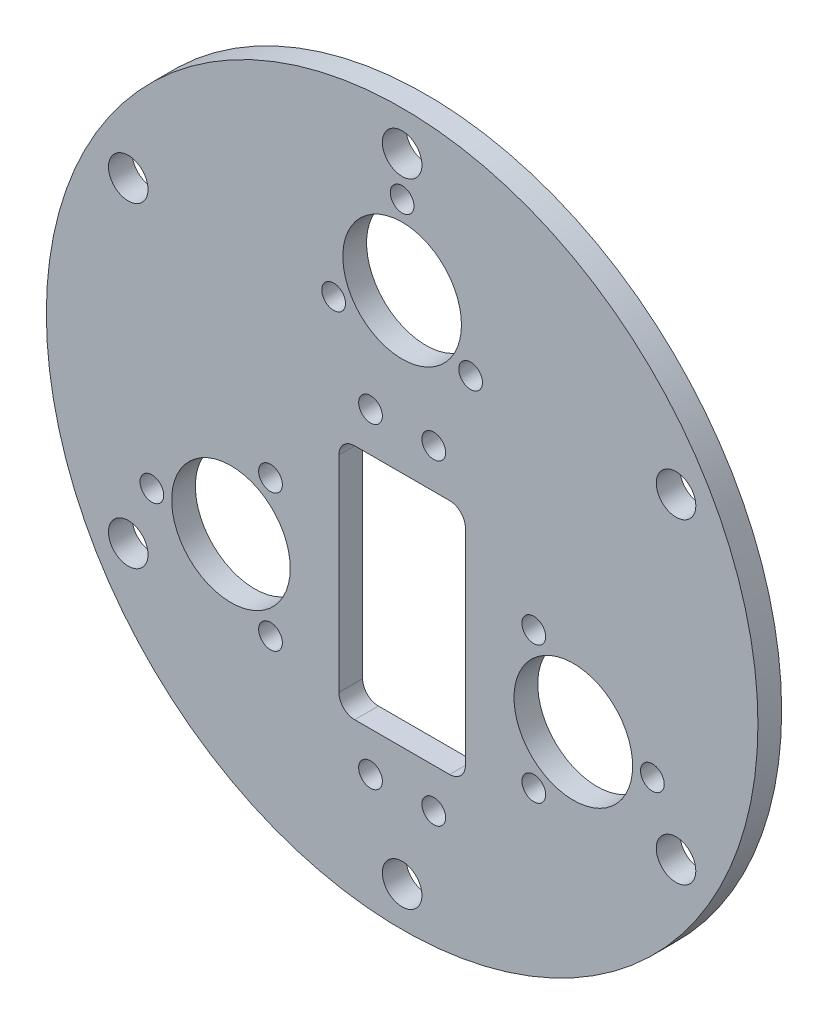
SolidWorks part; units mm, degrees
ref_plane "Front Plane" through (0, 0, 0) normal (0, 0, 1) x (1, 0, 0)
ref_plane "Top Plane" through (0, 0, 0) normal (0, 1, 0) x (1, 0, 0)
ref_plane "Right Plane" through (0, 0, 0) normal (1, 0, 0) x (0, 0, -1)
sketch "Sketch1" plane through (0, 0, 0) normal (0, 0, 1) x (1, 0, 0)
  circle A0 centre (0, 0) radius 4.5
  circle A2 centre (0, 2.5) radius 0.75
  circle A5 centre (2.1651, -1.25) radius 0.75
  circle A6 centre (-2.1651, -1.25) radius 0.75
  point P15 (0, 0)
  dimension "D1" = 9
  dimension "D3" = 1.5
  dimension "D6" = 3
extrude "Boss-Extrude1" add sketch "Sketch1" along normal blind 0.3
sketch "Sketch2" plane through (0, 0, 0.3) normal (0, 0, 1) x (1, 0, 0)
  circle A1 centre (0, -4) radius 0.25
  circle A2 centre (-3.4641, -2) radius 0.25
  circle A3 centre (-3.4641, 2) radius 0.25
  circle A4 centre (0, 4) radius 0.25
  circle A5 centre (3.4641, 2) radius 0.25
  circle A6 centre (3.4641, -2) radius 0.25
  point P18 (0, 0)
  dimension "D2" = 0.5
  dimension "D3" = 6
extrude "Cut-Extrude1" cut sketch "Sketch2" against normal blind 0.3
sketch "Sketch3" plane through (0, 0, 0.3) normal (0, 0, 1) x (1, 0, 0)
  line L0 (0, 4) -> (0, 0.5) construction
  line L1 (0, 0.5) -> (0, -2.5) construction
  line L2 (0, -2.5) -> (0, -4) construction
  line L3 (-0.8, 0.5) -> (-0.8, -2.5)
  line L4 (0.8, 0.5) -> (0.8, -2.5)
  line L5 (-0.8, 0.5) -> (0.8, 0.5)
  line L6 (-0.8, -2.5) -> (0.8, -2.5)
  dimension "D1" = 3.5
  dimension "D2" = 3
  dimension "D3" = 0.8
  dimension "D4" = 0.8
extrude "Cut-Extrude2" cut sketch "Sketch3" against normal blind 0.3
fillet "Fillet1" radius 0.2 4 edges at (-0.8, -2.5, 0.15) (0.8, -2.5, 0.15) (0.8, 0.5, 0.15) (-0.8, 0.5, 0.15)
sketch "Sketch4" plane through (0, 0, 0.3) normal (0, 0, 1) x (1, 0, 0)
  circle A0 centre (0, 2.5) radius 1
  circle A1 centre (0, 3.5) radius 0.15
  dimension "D1" = 2
  dimension "D2" = 0.3
extrude "Cut-Extrude3" cut sketch "Sketch4" against normal blind 0.3 contours A1
pattern_circular "CirPattern1" count 3 every 120 about axis through (0, 2.5, 0) along (0, 0, 1) of "Cut-Extrude3"
sketch "Sketch5" plane through (0, 0, 0.3) normal (0, 0, 1) x (1, 0, 0)
  circle A0 centre (2.1651, -1.25) radius 1
  circle A1 centre (3.1651, -1.25) radius 0.15
  dimension "D1" = 2
  dimension "D2" = 0.3
extrude "Cut-Extrude4" cut sketch "Sketch5" against normal blind 0.3 contours A1
pattern_circular "CirPattern3" count 3 every 120 about axis through (2.1651, -1.25, 0) along (0, 0, 1) of "Cut-Extrude4"
sketch "Sketch6" plane through (0, 0, 0.3) normal (0, 0, 1) x (1, 0, 0)
  circle A0 centre (-2.1651, -1.25) radius 1
  circle A1 centre (-3.1651, -1.25) radius 0.15
  dimension "D1" = 2
  dimension "D2" = 0.3
extrude "Cut-Extrude5" cut sketch "Sketch6" against normal blind 0.3 contours A1
pattern_circular "CirPattern4" count 3 every 120 about axis through (-2.1651, -1.25, 0) along (0, 0, 1) of "Cut-Extrude5"
sketch "Sketch7" plane through (0, 0, 0.3) normal (0, 0, 1) x (1, 0, 0)
  line L0 (0, 1) -> (0, 0.5) construction
  line L1 (0.6, 0.5) -> (-0.6, 0.5) construction
  line L2 (0, 0.5) -> (0, -2.5) construction
  line L3 (-0.6, -2.5) -> (0.6, -2.5) construction
  line L4 (0, -2.5) -> (0, -3) construction
  circle A0 centre (0.4, -3) radius 0.15
  circle A1 centre (-0.4, -3) radius 0.15
  circle A2 centre (0.4, 1) radius 0.15
  circle A3 centre (-0.4, 1) radius 0.15
  dimension "D5" = 0.3
  dimension "D6" = 0.3
  dimension "D7" = 0.3
  dimension "D8" = 0.3
  dimension "D1" = 0.5
  dimension "D2" = 0.5
extrude "Cut-Extrude8" cut sketch "Sketch7" against normal blind 0.3
